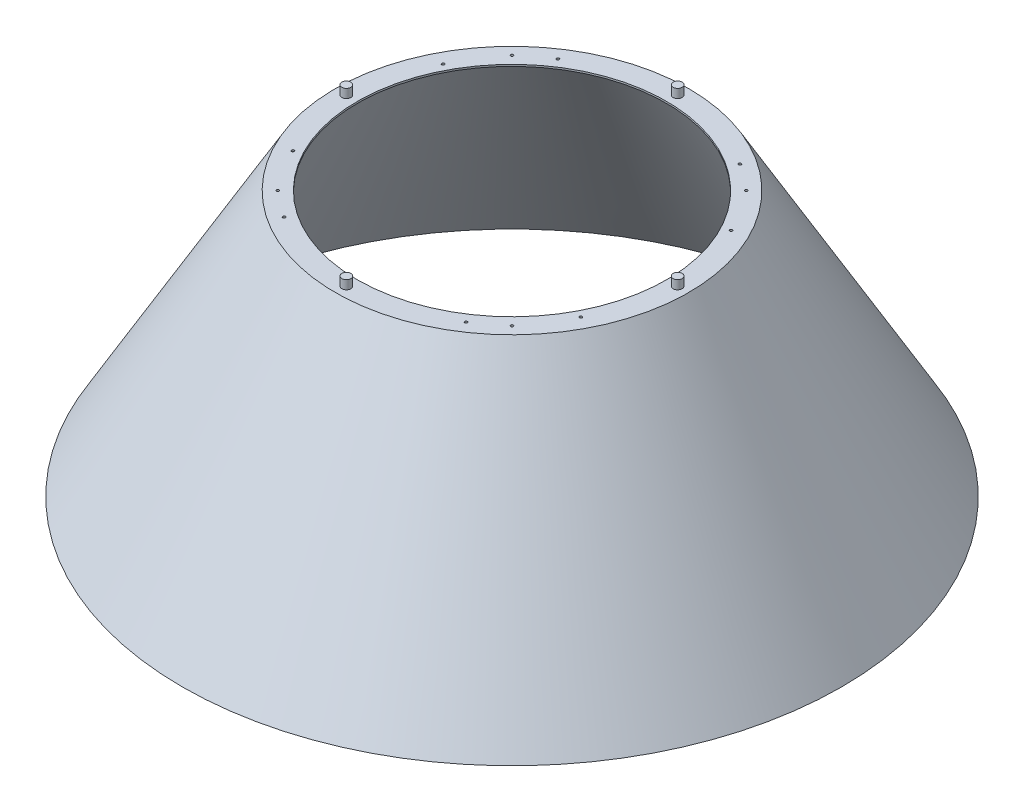
SolidWorks part; units mm, degrees
ref_plane "Front Plane" through (0, 0, 0) normal (0, 0, 1) x (1, 0, 0)
ref_plane "Top Plane" through (0, 0, 0) normal (0, 1, 0) x (1, 0, 0)
ref_plane "Right Plane" through (0, 0, 0) normal (1, 0, 0) x (0, 0, -1)
sketch "Sketch2" plane through (0, 263.6641, 0) normal (0, -1, 0) x (1, 0, 0)
  circle A1 centre (394.0867, 1032.5625) radius 200
  circle A2 centre (394.0867, 1032.5625) radius 200
  dimension "D1" = 0
extrude "Boss-Extrude1" add sketch "Sketch2" along normal blind 300 draft 30 draft outward yes
shell "Shell1" thickness 2
sketch "Sketch3" plane through (0, 263.6641, 0) normal (0, 1, 0) x (1, 0, 0)
  circle A1 centre (261.5041, -1165.145) radius 1.5
  circle A2 centre (261.5041, -1165.145) radius 1.5
  circle A3 centre (526.6692, -1165.145) radius 1.5
  circle A4 centre (526.6692, -1165.145) radius 1.5
  circle A5 centre (526.6692, -899.9799) radius 1.5
  circle A6 centre (526.6692, -899.9799) radius 1.5
  circle A7 centre (261.5041, -899.9799) radius 1.5
  circle A8 centre (261.5041, -899.9799) radius 1.5
  circle A9 centre (206.5867, -1032.5625) radius 5.1
  circle A10 centre (206.5867, -1032.5625) radius 5.1 construction
  circle A11 centre (394.0867, -1220.0625) radius 5.1
  circle A12 centre (394.0867, -1220.0625) radius 5.1 construction
  circle A13 centre (581.5867, -1032.5625) radius 5.1
  circle A14 centre (581.5867, -1032.5625) radius 5.1 construction
  circle A15 centre (394.0867, -845.0625) radius 5.1
  circle A16 centre (394.0867, -845.0625) radius 5.1 construction
  circle A17 centre (394.0867, -1032.5625) radius 175
  circle A18 centre (394.0867, -1032.5625) radius 175
  dimension "D1" = 0
  dimension "D2" = 0
  dimension "D3" = 0
  dimension "D4" = 0
  dimension "D5" = 0
  dimension "D6" = 0
  dimension "D7" = 0
  dimension "D8" = 0
  dimension "D9" = 0
extrude "Cut-Extrude1" cut sketch "Sketch3" against normal up to next
sketch "Sketch4" plane through (0, 263.6641, 0) normal (0, 1, 0) x (1, 0, 0)
  circle A0 centre (206.5867, -1032.5625) radius 5.1 construction
  circle A1 centre (394.0867, -845.0625) radius 5.1 construction
  circle A2 centre (581.5867, -1032.5625) radius 5.1 construction
  circle A3 centre (394.0867, -1220.0625) radius 5.1 construction
  circle A4 centre (206.5867, -1032.5625) radius 5.1
  circle A5 centre (394.0867, -845.0625) radius 5.1
  circle A6 centre (581.5867, -1032.5625) radius 5.1
  circle A7 centre (394.0867, -1220.0625) radius 5.1
extrude "Boss-Extrude2" add sketch "Sketch4" along normal blind 10
sketch "Sketch5" plane through (0, 263.6641, 0) normal (0, 1, 0) x (1, 0, 0)
  circle A1 centre (231.0867, -1117.5625) radius 1.5
  circle A2 centre (231.0867, -1117.5625) radius 1.5
  circle A3 centre (557.0867, -1117.5625) radius 1.5
  circle A4 centre (557.0867, -1117.5625) radius 1.5
  circle A5 centre (497.0867, -1187.5625) radius 1.5
  circle A6 centre (497.0867, -1187.5625) radius 1.5
  circle A7 centre (557.0867, -947.5625) radius 1.5
  circle A8 centre (557.0867, -947.5625) radius 1.5
  circle A9 centre (497.0867, -877.5625) radius 1.5
  circle A10 centre (497.0867, -877.5625) radius 1.5
  circle A11 centre (291.0867, -877.5625) radius 1.5
  circle A12 centre (291.0867, -877.5625) radius 1.5
  circle A13 centre (231.0867, -947.5625) radius 1.5
  circle A14 centre (231.0867, -947.5625) radius 1.5
  circle A15 centre (291.0867, -1187.5625) radius 1.5
  circle A16 centre (291.0867, -1187.5625) radius 1.5
  dimension "D1" = 0
  dimension "D2" = 0
  dimension "D3" = 0
  dimension "D4" = 0
  dimension "D5" = 0
  dimension "D6" = 0
  dimension "D7" = 0
  dimension "D8" = 0
extrude "Cut-Extrude4" cut sketch "Sketch5" against normal up to next
